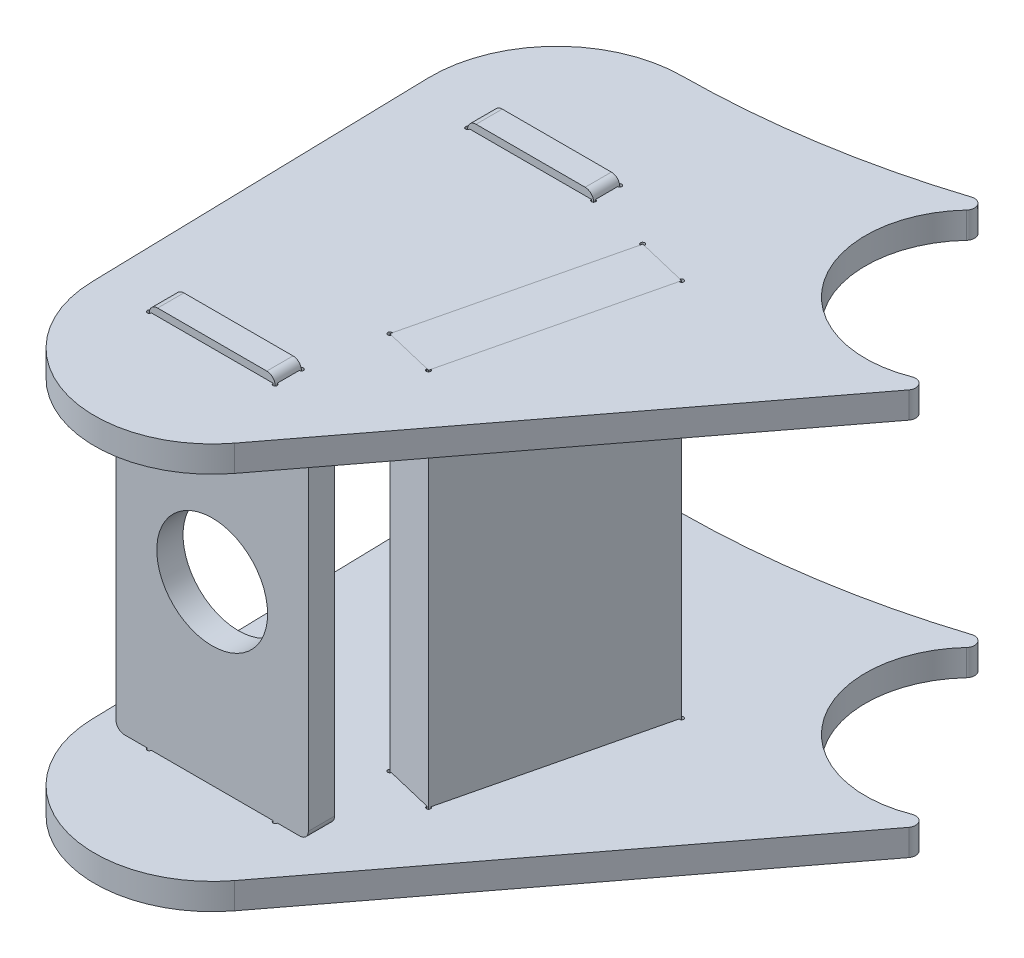
SolidWorks part; units mm, degrees
ref_plane "Front Plane" through (0, 0, 0) normal (0, 0, 1) x (1, 0, 0)
ref_plane "Top Plane" through (0, 0, 0) normal (0, 1, 0) x (1, 0, 0)
ref_plane "Right Plane" through (0, 0, 0) normal (1, 0, 0) x (0, 0, -1)
ref_plane "Plane2" through (0, 0, 17.4) normal (0, 0, 1) x (1, 0, 0)
sketch "Sketch2" plane through (0, 0, 17.4) normal (0, 0, 1) x (1, 0, 0)
  line L1 (-10.4542, 21) -> (-8.5, 21)
  line L2 (-11.4542, 20) -> (-11.4542, -20)
  line L3 (-10.4542, -21) -> (-8.5, -21)
  line L4 (11.4542, 20) -> (11.4542, -20)
  line L5 (-11.4542, 21) -> (11.4542, -21) construction
  line L6 (-11.4542, -21) -> (11.4542, 21) construction
  line L7 (-7.5, 22) -> (-7.5, 24)
  line L8 (7.5, 22) -> (7.5, 24)
  line L9 (-6.5, 25) -> (6.5, 25)
  line L10 (0, 25) -> (0, -25) construction
  line L11 (8.5, 21) -> (10.4542, 21)
  line L12 (-11.4542, 0) -> (11.4542, 0) construction
  line L13 (-11.4542, 21) -> (11.4542, -21) construction
  line L14 (-11.4542, -21) -> (11.4542, 21) construction
  line L15 (8.5, -21) -> (10.4542, -21)
  line L16 (-6.5, -25) -> (6.5, -25)
  line L17 (7.5, -22) -> (7.5, -24)
  line L18 (-7.5, -22) -> (-7.5, -24)
  line L19 (-11.4542, 21) -> (-8.5, 21)
  line L20 (-11.4542, -21) -> (-8.5, -21)
  line L21 (8.5, -21) -> (11.4542, -21)
  line L22 (8.5, 21) -> (11.4542, 21)
  circle A0 centre (0, 0) radius 6.6
  arc A1 (7.5, 24) -> (6.5, 25) centre (6.5, 24) ccw
  arc A2 (-7.5, 24) -> (-6.5, 25) centre (-6.5, 24) cw
  arc A3 (8.5, 21) -> (7.5, 22) centre (8.5, 22) cw
  arc A4 (-7.5, 22) -> (-8.5, 21) centre (-8.5, 22) cw
  arc A5 (-7.5, -22) -> (-8.5, -21) centre (-8.5, -22) ccw
  arc A6 (8.5, -21) -> (7.5, -22) centre (8.5, -22) ccw
  arc A7 (-7.5, -24) -> (-6.5, -25) centre (-6.5, -24) ccw
  arc A8 (7.5, -24) -> (6.5, -25) centre (6.5, -24) cw
  arc A9 (10.4542, -21) -> (11.4542, -20) centre (10.4542, -20) ccw
  arc A10 (-11.4542, -20) -> (-10.4542, -21) centre (-10.4542, -20) ccw
  arc A11 (10.4542, 21) -> (11.4542, 20) centre (10.4542, 20) cw
  arc A12 (-10.4542, 21) -> (-11.4542, 20) centre (-10.4542, 20) ccw
  point P20 (7.5, 21)
  point P36 (7.5, -21)
  point P37 (7.8195, -23.6747)
  dimension "D1" = 13.2
  dimension "D2" = 1
  dimension "D7" = 1
  dimension "D3" = 15
  dimension "D4" = 22.9084
  dimension "D5" = 50
  dimension "D6" = 4
extrude "Boss-Extrude1" add sketch "Sketch2" along normal blind 3.125 contours L1 A12 L2 A10 L3 A5 L18 A7 L16 A8 L17 A6 L15 A9 L4 A11 L11 L19 A0
mirror "Mirror4" about plane through (0, 0, 0) normal (0, 0, 1) of bodies 101 103
sketch "Sketch3" plane through (0, 21, 0) normal (0, 1, 0) x (1, 0, 0)
  line L0 (0, 0) -> (40, 0) construction
  line L1 (40, 0) -> (40, 30) construction
  line L2 (0, 20.525) -> (0, -20.525) construction
  line L4 (-14.9955, 20.1596) -> (-13.9958, -20.866)
  line L6 (45.8038, 16.6431) -> (11.1496, -28.9918)
  line L7 (-6.5, -20.525) -> (6.5, -20.525) construction
  line L8 (-6.5, 20.525) -> (6.5, 20.525) construction
  line L14 (-7.25, 17.4) -> (7.25, 17.4)
  line L15 (-7.5, 17.65) -> (-7.5, 20.275)
  line L16 (-7.25, 20.525) -> (7.25, 20.525)
  line L17 (7.5, 17.65) -> (7.5, 20.275)
  line L23 (-14.4957, -0.3532) -> (0, 0) construction
  line L30 (-6.5, 17.4) -> (6.5, 17.4) construction
  line L36 (-7.5, 20.525) -> (-7.5, 17.4) construction
  line L37 (29.9596, 39.3209) -> (45.0074, 17.2479) construction
  line L38 (8.5, 20.525) -> (7.5, 20.525) construction
  line L39 (37.4835, 28.2844) -> (29.5065, 22.8462) construction
  line L40 (7.5, 20.525) -> (7.5, 17.4) construction
  line L41 (7.5, 20.525) -> (6.5, 20.525) construction
  line L42 (-7.5, -17.65) -> (-7.5, -20.275)
  line L43 (-7.25, -20.525) -> (7.25, -20.525)
  line L44 (7.5, -17.65) -> (7.5, -20.275)
  line L45 (-7.25, -17.4) -> (7.25, -17.4)
  arc A0 (30.6924, 38.6406) -> (44.6419, 18.1787) centre (40, 30) ccw
  arc A1 (-0.1047, 35.5246) -> (-14.9955, 20.1596) centre (0, 20.525) ccw
  arc A2 (-13.9958, -20.866) -> (11.1496, -28.9918) centre (0, -20.525) ccw
  arc A3 (45.8038, 16.6431) -> (44.6419, 18.1787) centre (45.0074, 17.2479) ccw
  arc A5 (7.5, 20.275) -> (7.25, 20.525) centre (7.5, 20.525) ccw
  arc A6 (7.25, 17.4) -> (7.5, 17.65) centre (7.5, 17.4) ccw
  arc A7 (-7.5, 17.65) -> (-7.25, 17.4) centre (-7.5, 17.4) ccw
  arc A8 (-7.25, 20.525) -> (-7.5, 20.275) centre (-7.5, 20.525) ccw
  arc A17 (-7.25, -20.525) -> (-7.5, -20.275) centre (-7.5, -20.525) cw
  arc A18 (7.5, -20.275) -> (7.25, -20.525) centre (7.5, -20.525) cw
  arc A19 (7.25, -17.4) -> (7.5, -17.65) centre (7.5, -17.4) cw
  arc A20 (-7.5, -17.65) -> (-7.25, -17.4) centre (-7.5, -17.4) cw
  arc A21 (30.6924, 38.6406) -> (29.655, 40.2734) centre (29.9596, 39.3209) ccw
  arc A22 (29.655, 40.2734) -> (-0.1047, 35.5246) centre (-0.8027, 135.5222) cw
  point P7 (0, 0)
  point P14 (-1.651, 35.434)
  point P23 (29.6393, 41.1354)
  point P24 (-0.8674, 35.4999)
  point P35 (-9.8255, 20.275)
  point P38 (29.5065, 22.8462)
  point P39 (-9.9974, 25.2951)
  point P40 (37.5154, 30.2386)
  point P42 (0, 0)
  point P45 (29.6393, 41.1354)
  point P46 (29.0474, 41.8046)
  point P47 (-9.8255, 20.275)
  point P48 (-9.8255, 20.275)
  point P55 (30.5357, 40.4686)
  point P56 (29.0474, 41.8046)
  point P57 (29.7905, 41.1354)
  point P58 (-3.3013, 35.2509)
  point P59 (0, 0)
  point P60 (0, 0)
  point P61 (29.4297, 41.1354)
  point P62 (29.4297, 41.1354)
  point P63 (0, 35.5246)
  line B0 (14.8774, 15.6017) -> (9.1505, -8.2226)
  line B1 (14.9259, -9.868) -> (9.3351, -8.5241)
  line B2 (20.9536, 14.1381) -> (15.2274, -9.6834)
  line B3 (20.7689, 14.4396) -> (15.1409, 15.7924)
  arc B4 (9.3351, -8.5241) -> (9.1505, -8.2226) centre (9.092, -8.4657) cw
  arc B5 (15.2274, -9.6834) -> (14.9259, -9.868) centre (15.1689, -9.9264) cw
  arc B6 (20.7689, 14.4396) -> (20.9536, 14.1381) centre (21.012, 14.3811) cw
  arc B7 (14.8774, 15.6017) -> (15.1409, 15.7924) centre (14.8978, 15.8509) cw
  dimension "D1" = 25.4
  dimension "D4" = 1
  dimension "D5" = 15
  dimension "D6" = 14
  dimension "D10" = 0.5
  dimension "D7" = 1
  dimension "D9" = 100
  dimension "D2" = 40
  dimension "D3" = 30
sketch_block_instance "Block1-1"
sketch_block "Block1" parameters "D1"=6.25, "D2"=25
extrude "Boss-Extrude2" add sketch "Sketch3" along normal blind 3.125 separate body
mirror "Mirror5" about plane through (0, 0, 0) normal (0, 1, 0) of bodies 105
sketch "Sketch4" plane through (0, 24.125, 0) normal (0, 1, 0) x (1, 0, 0)
  line L0 (9.092, -8.4657) -> (15.1689, -9.9264)
  line L1 (9.092, -8.4657) -> (14.9351, 15.8419)
  line L2 (15.1689, -9.9264) -> (21.012, 14.3811)
  line L3 (14.9351, 15.8419) -> (21.012, 14.3811)
  line L4 (15.2274, -9.6834) -> (20.9536, 14.1381) construction
  line L5 (20.7689, 14.4396) -> (15.1409, 15.7924) construction
  line L6 (9.3351, -8.5241) -> (14.9259, -9.868) construction
  line L7 (14.8774, 15.6017) -> (9.1505, -8.2226) construction
extrude "Boss-Extrude3" add sketch "Sketch4" against normal up to surface (48.25 mm away) separate body up to face at (14.9968, -24.125, -13.4895)
